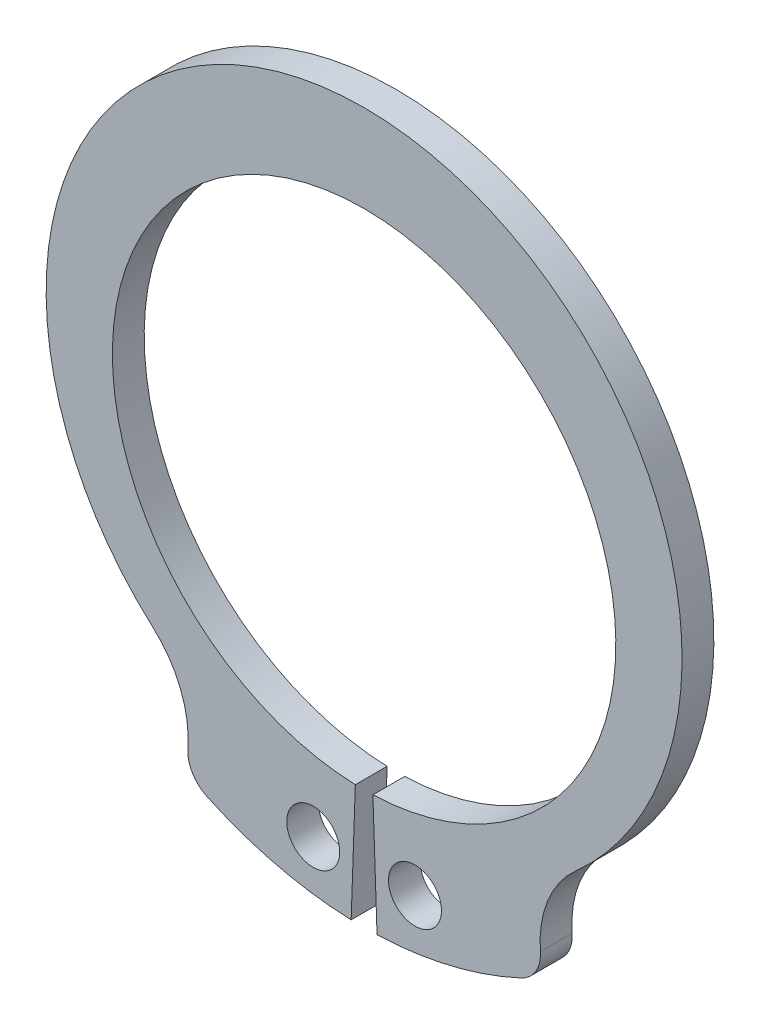
SolidWorks part; units mm, degrees
ref_plane "Front Plane" through (0, 0, 0) normal (0, 0, 1) x (1, 0, 0)
ref_plane "Top Plane" through (0, 0, 0) normal (0, 1, 0) x (1, 0, 0)
ref_plane "Right Plane" through (0, 0, 0) normal (1, 0, 0) x (0, 0, -1)
sketch "Sketch2" plane through (0, 0, 0) normal (0, 0, 1) x (1, 0, 0)
  line L0 (0, 0) -> (0, -23.75) construction
  line L1 (0, 0) -> (6.5464, -22.83)
  line L2 (0, 0) -> (-6.5464, -22.83)
  circle A0 centre (0, 0) radius 23.75
  circle A1 centre (0, -1.4) radius 20.75
  circle A6 centre (-7.7551, -17.9755) radius 2.5
  circle A7 centre (-11.896, -11.7222) radius 5
  circle A9 centre (0, -1.4) radius 15.8
  circle A10 centre (-7.7551, -17.9755) radius 1
  circle A11 centre (7.7551, -17.9755) radius 1
  circle A12 centre (7.7551, -17.9755) radius 2.5
  circle A13 centre (11.896, -11.7222) radius 5
  dimension "D1" = 47.5
  dimension "D5" = 41.5
  dimension "D2" = 10
  dimension "D6" = 5
  dimension "D7" = 31.6
  dimension "D8" = 2
  dimension "D3" = 32
  dimension "D4" = 1.4
sketch "Sketch3" plane through (0, 0, 0) normal (0, 0, 1) x (1, 0, 0)
  line L0 (0, 0) -> (0, -16.3969) construction
  line L1 (0, 0) -> (0.4886, -13.9915)
  line L2 (0, 0) -> (-0.4886, -13.9915)
  circle A0 centre (0, 0) radius 9.5
  circle A1 centre (0, 0) radius 14
  circle A2 centre (0, 0.8) radius 12
  circle A3 centre (10.6411, -11.1485) radius 4
  circle A4 centre (5.4063, -11.5471) radius 1.25
  circle A5 centre (1.9197, -11.9915) radius 1
  circle A6 centre (-10.6411, -11.1485) radius 4
  circle A7 centre (-5.4063, -11.5471) radius 1.25
  circle A8 centre (-1.9197, -11.9915) radius 1
  dimension "D1" = 19
  dimension "D2" = 24
  dimension "D3" = 0.8
  dimension "D4" = 28
  dimension "D7" = 2.5
  dimension "D8" = 8
  dimension "D11" = 2
  dimension "D5" = 2
  dimension "D6" = 5
  dimension "D9" = 1.5
  dimension "D10" = 2
extrude "Boss-Extrude1" add sketch "Sketch3" along normal blind 1.2 contours A2 A8 L2 A0 L1 A5 | A2 A8 A6 A7 A1 L2 | A7 | A5 A2 L1 A1 A4 A3 | A4
equation "\"D1@Sketch2\" = \"G_anneau_alesage_rouleau\""
equation "\"c_anneau\"=31.6"
equation "\"D5@Sketch2\" = \"G_anneau_alesage_rouleau\" - 6"
equation "\"e_anneau\"=1.75"
equation "\"D2@Sketch2\"=2*\"D6@Sketch2\""
equation "\"D7@Sketch2\"=\"c_anneau\""
equation "\"d_ext_rouleau\"= 120"
equation "\"epaisseur_rouleau\"=80"
equation "\"alesage-rouleau\"= 52"
equation "\"jeu_dent_rouleau\"= 2"
equation "\"profondeur_dent_rouleau\"=4"
equation "\"n_dent_roueau\"= 15"
equation "\"d_ext_roulement_rouleau\"= 42"
equation "\"d_int_roulement_rouleau\"= 20"
equation "\"B_roulement_rouleau\"= 12"
equation "\"r_roulement_rouleau\"= 0.6"
equation "\"d_bille_roulement_rouleau\"= 8"
equation "\"F_anneau_alesage_rouleau\"=1.85"
equation "\"G_anneau_alesage_rouleau\"=47.5"
equation "\"K_anneau_alesage_rouleau\"=3.75"
equation "\"d_vis_flasque_rouleau\"=5"
equation "\"l-x_vis_flasque_rouleau\"=4"
equation "\"g_anneau_arbre_rouleau\"=19"
equation "\"f_anneau_arbre_rouleau\"=1.3"
equation "\"k_anneau_arbre_rouleau\"=1.5"
equation "\"h_matrice\"= 15"
equation "\"d_matrice\"= 250"
equation "\"d_granulat\"= 8"
equation "\"zone_vide_matrice\" = 70"
equation "\"d_alesage_matrice\"=50"
equation "\"a_clavette_alesage_matrice\"=16"
equation "\"entrax_vis_rouleau\"=86"
